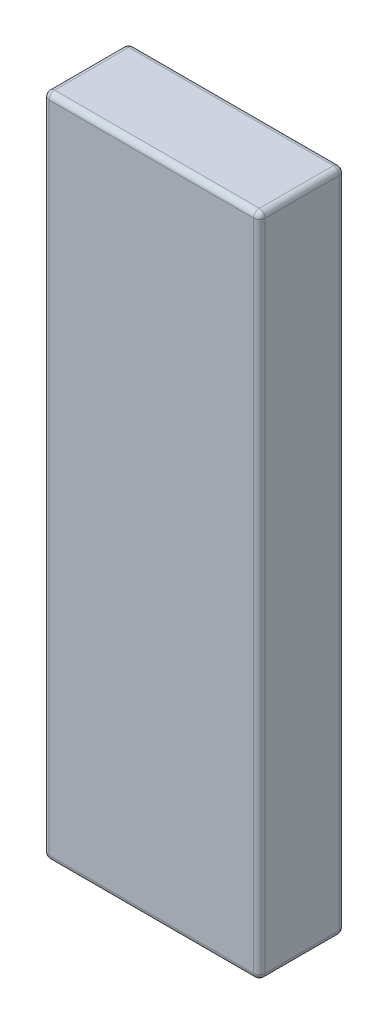
SolidWorks part; units mm, degrees
ref_plane "Front Plane" through (0, 0, 0) normal (0, 0, 1) x (1, 0, 0)
ref_plane "Top Plane" through (0, 0, 0) normal (0, 1, 0) x (1, 0, 0)
ref_plane "Right Plane" through (0, 0, 0) normal (1, 0, 0) x (0, 0, -1)
sketch "Sketch1" plane through (0, 0, 0) normal (0, 0, 1) x (1, 0, 0)
  line L1 (-1.9, 5.85) -> (1.9, 5.85)
  line L2 (-1.9, 5.85) -> (-1.9, -5.85)
  line L3 (-1.9, -5.85) -> (1.9, -5.85)
  line L4 (1.9, 5.85) -> (1.9, -5.85)
  line L5 (-1.9, 5.85) -> (1.9, -5.85) construction
  line L6 (-1.9, -5.85) -> (1.9, 5.85) construction
  point P0 (0, 0)
  dimension "D1" = 3.8
  dimension "D2" = 11.7
extrude "Boss-Extrude1" add sketch "Sketch1" along normal blind 1.5
fillet "Fillet1" radius 0.1 12 edges at (-1.9, -5.85, 0.75) (-1.9, 5.85, 0.75) (1.9, -5.85, 0.75) (1.9, 5.85, 0.75) (0, 5.85, 0) (-1.9, 0, 0) (0, -5.85, 0) (1.9, 0, 0) (0, -5.85, 1.5) (-1.9, 0, 1.5) (0, 5.85, 1.5) (1.9, 0, 1.5)
